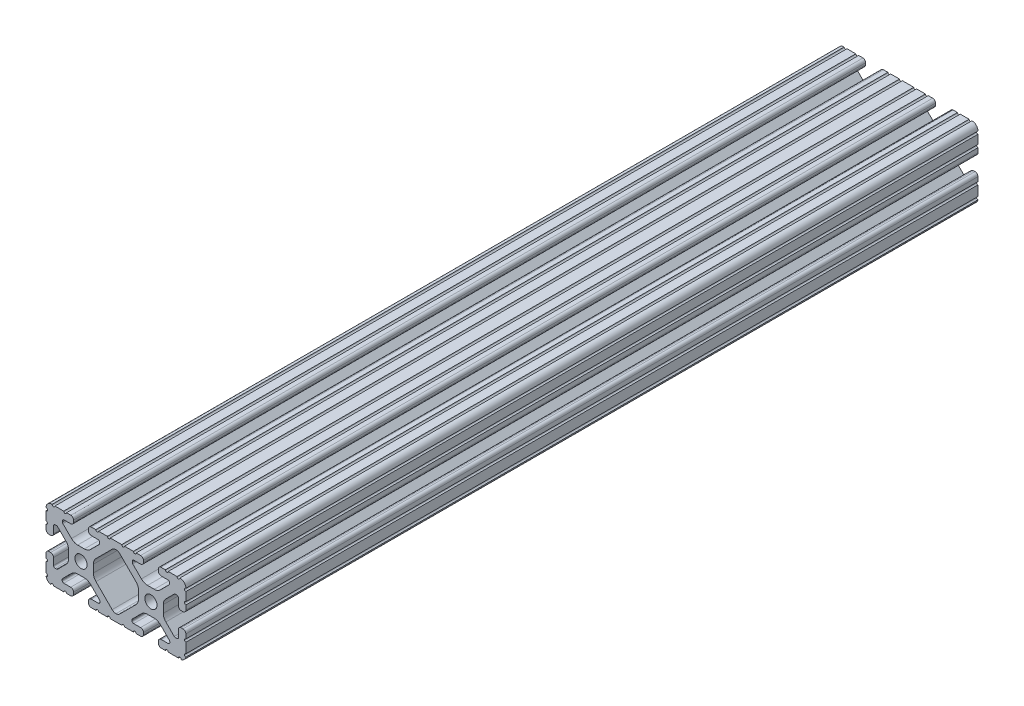
SolidWorks part; units mm, degrees
material "6005A-T61"
ref_plane "Front Plane" through (0, 0, 0) normal (0, 0, 1) x (1, 0, 0)
ref_plane "Top Plane" through (0, 0, 0) normal (0, 1, 0) x (1, 0, 0)
ref_plane "Right Plane" through (0, 0, 0) normal (1, 0, 0) x (0, 0, -1)
sketch "Sketch1" plane through (0, 0, 0) normal (0, 0, 1) x (1, 0, 0)
  line L0 (-3.1211, -19.05) -> (3.1211, -19.05)
  line L1 (-38.1, 10.287) -> (-38.1, 14.3752)
  line L2 (0, -34.5561) -> (0, 32.8014) construction
  line L3 (-38.1, 0) -> (0, 0) construction
  line L4 (-38.1, 9.5497) -> (-38.1, 10.287)
  line L5 (-19.05, 19.05) -> (-19.05, -20.2827) construction
  line L6 (0, -15.1247) -> (0, -15.1131) construction
  line L7 (9.1761, 12.9058) -> (13.8525, 8.2294)
  line L8 (8.9158, 14.097) -> (8.9158, 13.5344)
  line L9 (13.4112, 14.986) -> (9.8048, 14.986)
  line L10 (14.986, 17.4968) -> (14.986, 16.5608)
  line L11 (10.9975, 19.05) -> (13.4328, 19.05)
  line L12 (8.6331, 19.05) -> (9.4735, 19.05)
  line L13 (4.6451, 19.05) -> (8.6331, 19.05)
  line L14 (31.792, 10.0266) -> (27.1976, 5.4321)
  line L15 (33.147, 10.287) -> (32.4207, 10.287)
  line L16 (29.2071, 19.05) -> (33.2963, 19.05)
  line L17 (28.4698, 19.05) -> (29.2071, 19.05)
  line L18 (-38.1, 5.6388) -> (-38.1, 8.0257)
  line L19 (24.5589, 19.05) -> (26.9458, 19.05)
  line L20 (23.114, 16.5608) -> (23.114, 17.4806)
  line L21 (28.2952, 14.986) -> (24.6888, 14.986)
  line L22 (29.1842, 13.5344) -> (29.1842, 14.097)
  line L23 (-34.036, 9.398) -> (-34.036, 5.6388)
  line L24 (-35.6108, 4.064) -> (-36.5252, 4.064)
  line L25 (24.2475, 8.2294) -> (28.9239, 12.9058)
  line L26 (25.8064, -2.0735) -> (25.8064, 2.0735)
  line L27 (35.6108, 4.064) -> (36.5252, 4.064)
  line L28 (34.036, 9.398) -> (34.036, 5.6388)
  line L29 (38.1, 5.6388) -> (38.1, 8.0257)
  line L30 (38.1, 9.5497) -> (38.1, 10.287)
  line L31 (38.1, 10.287) -> (38.1, 14.3752)
  line L32 (17.2111, 6.8382) -> (20.8889, 6.8382)
  line L33 (2.077, 14.2576) -> (10.9024, 5.4321)
  line L34 (-31.792, -10.0266) -> (-27.1976, -5.4321)
  line L35 (-33.147, -10.287) -> (-32.4207, -10.287)
  line L36 (-29.2071, -19.05) -> (-34.0473, -19.05)
  line L37 (-28.4698, -19.05) -> (-29.2071, -19.05)
  line L38 (-24.6888, -19.05) -> (-26.9458, -19.05)
  line L39 (12.2936, -2.0735) -> (12.2936, 2.0735)
  line L40 (-23.114, -16.5608) -> (-23.114, -17.4752)
  line L41 (-28.448, -14.986) -> (-24.6888, -14.986)
  line L42 (-29.337, -13.6872) -> (-29.337, -14.097)
  line L43 (2.077, -14.2576) -> (10.9024, -5.4321)
  line L44 (-3.1211, 19.05) -> (3.1211, 19.05)
  line L45 (8.763, -14.097) -> (8.763, -13.6872)
  line L46 (-24.2475, -8.2294) -> (-29.0766, -13.0586)
  line L47 (-35.6108, -4.064) -> (-36.5252, -4.064)
  line L48 (-34.036, -9.398) -> (-34.036, -5.6388)
  line L49 (-38.1, -5.6388) -> (-38.1, -8.0257)
  line L50 (-38.1, -9.5497) -> (-38.1, -10.287)
  line L51 (-38.1, -10.287) -> (-38.1, -15.036)
  line L52 (17.2111, -6.8382) -> (20.8889, -6.8382)
  line L53 (38.1, -10.287) -> (38.1, -15.036)
  line L54 (38.1, -9.5497) -> (38.1, -10.287)
  line L55 (38.1, -5.6388) -> (38.1, -8.0257)
  line L56 (34.036, -9.398) -> (34.036, -5.6388)
  line L57 (35.6108, -4.064) -> (36.5252, -4.064)
  line L58 (24.2475, -8.2294) -> (29.0766, -13.0586)
  line L59 (29.337, -13.6872) -> (29.337, -14.097)
  line L60 (-17.2111, -6.8382) -> (-20.8889, -6.8382)
  line L61 (-9.0234, -13.0586) -> (-13.8525, -8.2294)
  line L62 (-8.763, -14.097) -> (-8.763, -13.6872)
  line L63 (-13.4112, -14.986) -> (-9.652, -14.986)
  line L64 (-14.986, -17.4752) -> (-14.986, -16.5608)
  line L65 (-10.9975, -19.05) -> (-13.4112, -19.05)
  line L66 (28.448, -14.986) -> (24.6888, -14.986)
  line L67 (23.114, -16.5608) -> (23.114, -17.4752)
  line L68 (24.6888, -19.05) -> (26.9458, -19.05)
  line L69 (28.4698, -19.05) -> (29.2071, -19.05)
  line L70 (29.2071, -19.05) -> (34.0473, -19.05)
  line L71 (-8.6331, -19.05) -> (-9.4735, -19.05)
  line L72 (33.147, -10.287) -> (32.4207, -10.287)
  line L73 (31.792, -10.0266) -> (27.1976, -5.4321)
  line L74 (-4.6451, -19.05) -> (-8.6331, -19.05)
  line L75 (9.0234, -13.0586) -> (13.8525, -8.2294)
  line L76 (13.4112, -14.986) -> (9.652, -14.986)
  line L77 (-2.077, -14.2576) -> (-10.9024, -5.4321)
  line L78 (14.986, -17.4752) -> (14.986, -16.5608)
  line L79 (10.9975, -19.05) -> (13.4112, -19.05)
  line L80 (4.6451, -19.05) -> (8.6331, -19.05)
  line L81 (8.6331, -19.05) -> (9.4735, -19.05)
  line L83 (-12.2936, -2.0735) -> (-12.2936, 2.0735)
  line L84 (-25.8064, -2.0735) -> (-25.8064, 2.0735)
  line L85 (-2.077, 14.2576) -> (-10.9024, 5.4321)
  line L87 (-4.6451, 19.05) -> (-8.6331, 19.05)
  line L88 (-8.6331, 19.05) -> (-9.4735, 19.05)
  line L89 (-10.9975, 19.05) -> (-13.4328, 19.05)
  line L90 (-14.986, 17.4968) -> (-14.986, 16.5608)
  line L91 (-13.4112, 14.986) -> (-9.8048, 14.986)
  line L92 (-8.9158, 14.097) -> (-8.9158, 13.5344)
  line L93 (-9.1761, 12.9058) -> (-13.8525, 8.2294)
  line L94 (-17.2111, 6.8382) -> (-20.8889, 6.8382)
  line L95 (-24.2475, 8.2294) -> (-28.9239, 12.9058)
  line L96 (-29.1842, 13.5344) -> (-29.1842, 14.097)
  line L97 (-28.2952, 14.986) -> (-24.6888, 14.986)
  line L98 (-23.114, 16.5608) -> (-23.114, 17.4806)
  line L99 (-24.5589, 19.05) -> (-26.9458, 19.05)
  line L100 (-28.4698, 19.05) -> (-29.2071, 19.05)
  line L101 (-29.2071, 19.05) -> (-33.2963, 19.05)
  line L109 (-33.147, 10.287) -> (-32.4207, 10.287)
  line L165 (-31.792, 10.0266) -> (-27.1976, 5.4321)
  arc A0 (-38.1376, 15.8983) -> (-38.1, 14.3752) centre (-38.1, 15.1372) cw
  arc A1 (-38.1, 9.5497) -> (-38.1, 8.0257) centre (-38.1, 8.7877) cw
  arc A2 (9.1761, 12.9058) -> (8.9158, 13.5344) centre (9.8048, 13.5344) cw
  arc A3 (8.9158, 14.097) -> (9.8048, 14.986) centre (9.8048, 14.097) cw
  arc A4 (-36.5252, 4.064) -> (-38.1, 5.6388) centre (-36.5252, 5.6388) cw
  arc A5 (14.986, 16.5608) -> (13.4112, 14.986) centre (13.4112, 16.5608) cw
  arc A6 (13.4328, 19.05) -> (14.986, 17.4968) centre (13.4328, 17.4968) cw
  arc A7 (10.9975, 19.05) -> (9.4735, 19.05) centre (10.2355, 19.05) cw
  arc A8 (4.6451, 19.05) -> (3.1211, 19.05) centre (3.8831, 19.05) cw
  arc A9 (0, 15.1131) -> (2.077, 14.2576) centre (0.0116, 12.1921) cw
  arc A10 (25.8064, 2.0735) -> (27.1976, 5.4321) centre (30.5562, 2.0735) cw
  arc A11 (31.792, 10.0266) -> (32.4207, 10.287) centre (32.4207, 9.398) cw
  arc A12 (33.147, 10.287) -> (34.036, 9.398) centre (33.147, 9.398) cw
  arc A13 (34.8195, 19.0968) -> (38.1376, 15.8983) centre (34.903, 15.8631) cw
  arc A14 (34.8195, 19.0968) -> (33.2963, 19.05) centre (34.0579, 19.0734) cw
  arc A15 (28.4698, 19.05) -> (26.9458, 19.05) centre (27.7078, 19.05) cw
  arc A16 (23.114, 17.4806) -> (24.5589, 19.05) centre (24.6888, 17.4806) cw
  arc A17 (24.6888, 14.986) -> (23.114, 16.5608) centre (24.6888, 16.5608) cw
  arc A18 (28.2952, 14.986) -> (29.1842, 14.097) centre (28.2952, 14.097) cw
  arc A19 (29.1842, 13.5344) -> (28.9239, 12.9058) centre (28.2952, 13.5344) cw
  arc A20 (-35.5713, -19.05) -> (-38.1, -16.56) centre (-34.9455, -15.8855) cw
  arc A21 (34.036, 5.6388) -> (35.6108, 4.064) centre (35.6108, 5.6388) ccw
  arc A22 (36.5252, 4.064) -> (38.1, 5.6388) centre (36.5252, 5.6388) ccw
  arc A23 (38.1, 9.5497) -> (38.1, 8.0257) centre (38.1, 8.7877) ccw
  arc A24 (24.2475, 8.2294) -> (20.8889, 6.8382) centre (20.8889, 11.588) cw
  arc A25 (17.2111, 6.8382) -> (13.8525, 8.2294) centre (17.2111, 11.588) cw
  arc A26 (10.9024, 5.4321) -> (12.2936, 2.0735) centre (7.5438, 2.0735) cw
  arc A27 (0, -15.1131) -> (2.077, -14.2576) centre (0.0116, -12.1921) ccw
  arc A28 (-34.036, 5.6388) -> (-35.6108, 4.064) centre (-35.6108, 5.6388) cw
  arc A29 (-25.8064, -2.0735) -> (-27.1976, -5.4321) centre (-30.5562, -2.0735) cw
  arc A30 (-31.792, -10.0266) -> (-32.4207, -10.287) centre (-32.4207, -9.398) cw
  arc A31 (-33.147, -10.287) -> (-34.036, -9.398) centre (-33.147, -9.398) cw
  arc A33 (-35.5713, -19.05) -> (-34.0473, -19.05) centre (-34.8093, -19.05) cw
  arc A34 (-28.4698, -19.05) -> (-26.9458, -19.05) centre (-27.7078, -19.05) cw
  arc A35 (10.9024, -5.4321) -> (12.2936, -2.0735) centre (7.5438, -2.0735) ccw
  circle A36 centre (19.05, 0) radius 3.3274
  arc A37 (-23.114, -17.4752) -> (-24.6888, -19.05) centre (-24.6888, -17.4752) cw
  arc A38 (-24.6888, -14.986) -> (-23.114, -16.5608) centre (-24.6888, -16.5608) cw
  arc A39 (-28.448, -14.986) -> (-29.337, -14.097) centre (-28.448, -14.097) cw
  arc A40 (-29.337, -13.6872) -> (-29.0766, -13.0586) centre (-28.448, -13.6872) cw
  arc A41 (-24.2475, -8.2294) -> (-20.8889, -6.8382) centre (-20.8889, -11.588) cw
  arc A42 (-34.036, -5.6388) -> (-35.6108, -4.064) centre (-35.6108, -5.6388) ccw
  arc A43 (-36.5252, -4.064) -> (-38.1, -5.6388) centre (-36.5252, -5.6388) ccw
  arc A44 (-38.1, -9.5497) -> (-38.1, -8.0257) centre (-38.1, -8.7877) ccw
  arc A45 (-38.1, -16.56) -> (-38.1, -15.036) centre (-38.1, -15.798) ccw
  arc A46 (38.1, -16.56) -> (38.1, -15.036) centre (38.1, -15.798) cw
  arc A47 (38.1, -9.5497) -> (38.1, -8.0257) centre (38.1, -8.7877) cw
  arc A48 (36.5252, -4.064) -> (38.1, -5.6388) centre (36.5252, -5.6388) cw
  arc A49 (34.036, -5.6388) -> (35.6108, -4.064) centre (35.6108, -5.6388) cw
  arc A50 (24.2475, -8.2294) -> (20.8889, -6.8382) centre (20.8889, -11.588) ccw
  arc A51 (29.337, -13.6872) -> (29.0766, -13.0586) centre (28.448, -13.6872) ccw
  arc A52 (28.448, -14.986) -> (29.337, -14.097) centre (28.448, -14.097) ccw
  arc A53 (24.6888, -14.986) -> (23.114, -16.5608) centre (24.6888, -16.5608) ccw
  arc A54 (-17.2111, -6.8382) -> (-13.8525, -8.2294) centre (-17.2111, -11.588) cw
  arc A55 (-9.0234, -13.0586) -> (-8.763, -13.6872) centre (-9.652, -13.6872) cw
  arc A56 (-8.763, -14.097) -> (-9.652, -14.986) centre (-9.652, -14.097) cw
  arc A57 (-14.986, -16.5608) -> (-13.4112, -14.986) centre (-13.4112, -16.5608) cw
  arc A58 (-13.4112, -19.05) -> (-14.986, -17.4752) centre (-13.4112, -17.4752) cw
  arc A59 (-10.9975, -19.05) -> (-9.4735, -19.05) centre (-10.2355, -19.05) cw
  arc A60 (-4.6451, -19.05) -> (-3.1211, -19.05) centre (-3.8831, -19.05) cw
  arc A61 (23.114, -17.4752) -> (24.6888, -19.05) centre (24.6888, -17.4752) ccw
  arc A62 (28.4698, -19.05) -> (26.9458, -19.05) centre (27.7078, -19.05) ccw
  arc A63 (35.5713, -19.05) -> (34.0473, -19.05) centre (34.8093, -19.05) ccw
  arc A64 (35.5713, -19.05) -> (38.1, -16.56) centre (34.9379, -15.8778) ccw
  arc A65 (33.147, -10.287) -> (34.036, -9.398) centre (33.147, -9.398) ccw
  arc A66 (31.792, -10.0266) -> (32.4207, -10.287) centre (32.4207, -9.398) ccw
  arc A67 (-10.9024, -5.4321) -> (-12.2936, -2.0735) centre (-7.5438, -2.0735) cw
  arc A68 (0, -15.1131) -> (-2.077, -14.2576) centre (-0.0116, -12.1921) cw
  arc A69 (0, 15.1131) -> (-2.077, 14.2576) centre (-0.0116, 12.1921) ccw
  arc A70 (-10.9024, 5.4321) -> (-12.2936, 2.0735) centre (-7.5438, 2.0735) ccw
  arc A71 (25.8064, -2.0735) -> (27.1976, -5.4321) centre (30.5562, -2.0735) ccw
  arc A72 (9.0234, -13.0586) -> (8.763, -13.6872) centre (9.652, -13.6872) ccw
  arc A73 (8.763, -14.097) -> (9.652, -14.986) centre (9.652, -14.097) ccw
  arc A74 (17.2111, -6.8382) -> (13.8525, -8.2294) centre (17.2111, -11.588) ccw
  arc A75 (13.4112, -19.05) -> (14.986, -17.4752) centre (13.4112, -17.4752) ccw
  arc A76 (14.986, -16.5608) -> (13.4112, -14.986) centre (13.4112, -16.5608) ccw
  arc A77 (-4.6451, 19.05) -> (-3.1211, 19.05) centre (-3.8831, 19.05) ccw
  arc A78 (-10.9975, 19.05) -> (-9.4735, 19.05) centre (-10.2355, 19.05) ccw
  arc A79 (-13.4328, 19.05) -> (-14.986, 17.4968) centre (-13.4328, 17.4968) ccw
  arc A80 (-14.986, 16.5608) -> (-13.4112, 14.986) centre (-13.4112, 16.5608) ccw
  arc A81 (-8.9158, 14.097) -> (-9.8048, 14.986) centre (-9.8048, 14.097) ccw
  arc A82 (-9.1761, 12.9058) -> (-8.9158, 13.5344) centre (-9.8048, 13.5344) ccw
  arc A83 (-17.2111, 6.8382) -> (-13.8525, 8.2294) centre (-17.2111, 11.588) ccw
  arc A84 (-24.2475, 8.2294) -> (-20.8889, 6.8382) centre (-20.8889, 11.588) ccw
  arc A85 (-29.1842, 13.5344) -> (-28.9239, 12.9058) centre (-28.2952, 13.5344) ccw
  arc A86 (-28.2952, 14.986) -> (-29.1842, 14.097) centre (-28.2952, 14.097) ccw
  arc A87 (-24.6888, 14.986) -> (-23.114, 16.5608) centre (-24.6888, 16.5608) ccw
  arc A88 (-23.114, 17.4806) -> (-24.5589, 19.05) centre (-24.6888, 17.4806) ccw
  arc A89 (-28.4698, 19.05) -> (-26.9458, 19.05) centre (-27.7078, 19.05) ccw
  arc A90 (-34.8195, 19.0968) -> (-33.2963, 19.05) centre (-34.0579, 19.0734) ccw
  arc A91 (-34.8195, 19.0968) -> (-38.1376, 15.8983) centre (-34.903, 15.8631) ccw
  arc A92 (4.6451, -19.05) -> (3.1211, -19.05) centre (3.8831, -19.05) ccw
  arc A93 (10.9975, -19.05) -> (9.4735, -19.05) centre (10.2355, -19.05) ccw
  arc A94 (38.1376, 15.8983) -> (38.1, 14.3752) centre (38.1, 15.1372) ccw
  arc A96 (-33.147, 10.287) -> (-34.036, 9.398) centre (-33.147, 9.398) ccw
  arc A97 (-31.792, 10.0266) -> (-32.4207, 10.287) centre (-32.4207, 9.398) ccw
  arc A98 (-25.8064, 2.0735) -> (-27.1976, 5.4321) centre (-30.5562, 2.0735) ccw
  circle A101 centre (-19.05, 0) radius 3.3274
  point P34 (0, 19.05)
  point P79 (25.6765, 0)
  point P274 (0, -19.05)
  point P282 (-25.6765, 0)
  point P283 (-12.2936, 0)
  dimension "D1" = 38.1
  dimension "D4" = 6.6548
  dimension "D10" = 4.064
  dimension "D2" = 76.2
  dimension "D3" = 38.1
  dimension "D5" = 8.128
  dimension "D6" = 20.574
  dimension "D7" = 12.2936
  dimension "D8" = 4.064
  dimension "D9" = 4.064
extrude "Extrude1" add sketch "Sketch1" against normal blind 431.8
